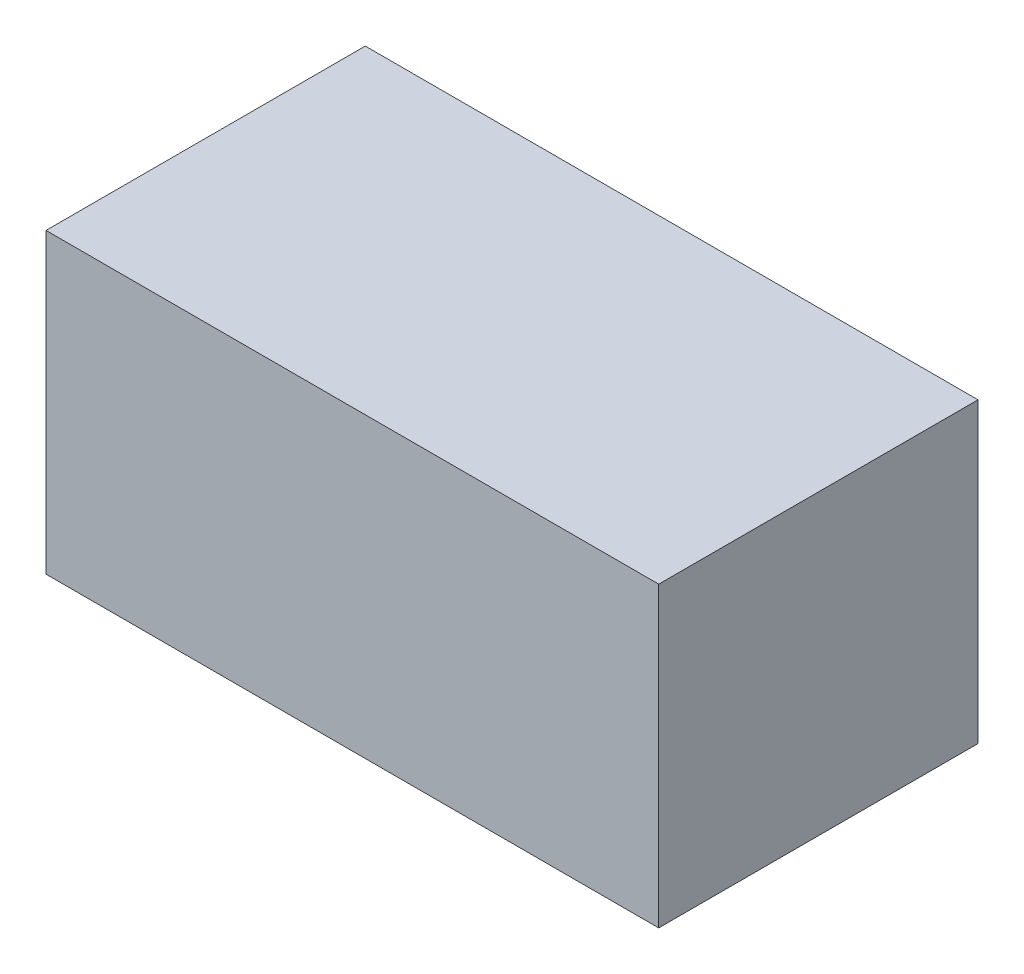
SolidWorks part; units mm, degrees
material "PA 类型 6"
ref_plane "前视基准面" through (0, 0, 0) normal (0, 0, 1) x (1, 0, 0)
ref_plane "上视基准面" through (0, 0, 0) normal (0, 1, 0) x (1, 0, 0)
ref_plane "右视基准面" through (0, 0, 0) normal (1, 0, 0) x (0, 0, -1)
other "Configuration Table"
sketch "草图1" plane through (0, 0, 0) normal (0, 1, 0) x (1, 0, 0)
  line L1 (-35.5, 18.5) -> (35.5, 18.5)
  line L2 (-35.5, 18.5) -> (-35.5, -18.5)
  line L3 (-35.5, -18.5) -> (35.5, -18.5)
  line L4 (35.5, 18.5) -> (35.5, -18.5)
  line L5 (-35.5, 18.5) -> (35.5, -18.5) construction
  line L6 (-35.5, -18.5) -> (35.5, 18.5) construction
  point P0 (0, 0)
  dimension "D1" = 71
  dimension "D2" = 37
extrude "凸台-拉伸1" add sketch "草图1" along normal blind 34.5
